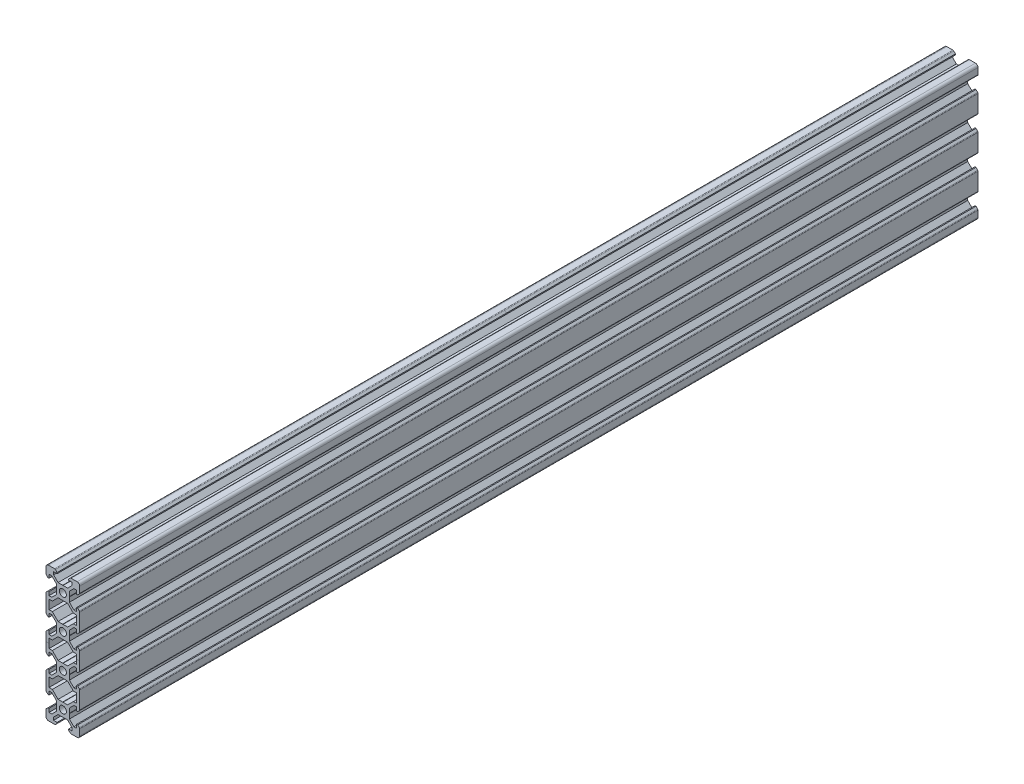
SolidWorks part; units mm, degrees
material "6063-T5"
ref_plane "Front" through (0, 0, 0) normal (0, 0, 1) x (1, 0, 0)
ref_plane "Top" through (0, 0, 0) normal (0, 1, 0) x (1, 0, 0)
ref_plane "Right" through (0, 0, 0) normal (1, 0, 0) x (0, 0, -1)
sketch "Sketch1" plane through (0, 0, 0) normal (0, 0, 1) x (1, 0, 0)
  line L0 (-8.5, 10) -> (-10, 8.5) construction
  line L1 (-8.5, 10) -> (-4.8628, 10)
  line L2 (-10, 8.5) -> (-10, 4.8628)
  line L3 (25.9287, -20) -> (-28.3599, -20) construction
  line L4 (10, 8.5) -> (10, 4.8628)
  line L5 (-10, 10) -> (10, -10) construction
  line L6 (-10, -10) -> (10, 10) construction
  line L7 (8.2, -5.5) -> (8.2, -3.3865)
  line L8 (-8.2, -5.5) -> (-8.2, -3.3865)
  line L9 (-5.5, 8.2) -> (-3.3865, 8.2)
  line L10 (-8.2, -12.7) -> (-8.2, -7.3)
  line L11 (-3.9005, 2.8395) -> (-6.561, 5.5)
  line L12 (-6.561, 5.5) -> (-8.2, 5.5)
  line L13 (-2.8395, -3.9005) -> (-0.1, -3.9005)
  line L14 (-3.9005, -2.8395) -> (-3.9005, -0.1)
  line L15 (-2.8395, 3.9005) -> (-0.1, 3.9005)
  line L16 (3.9005, -2.8395) -> (3.9005, -0.1)
  line L17 (-8.2, 3.3865) -> (-8.81, 3.3865)
  line L18 (-8.81, 3.3865) -> (-9.7976, 4.3741)
  line L19 (8.5, 10) -> (10, 8.5) construction
  line L20 (-2.8395, 3.9005) -> (-5.5, 6.561)
  line L21 (-5.5, 6.561) -> (-5.5, 8.2)
  line L22 (-3.3865, 8.2) -> (-3.3865, 8.81)
  line L23 (-3.3865, 8.81) -> (-4.3741, 9.7976)
  line L24 (0, 24.069) -> (0, -33.8154) construction
  line L25 (3.3865, 8.81) -> (4.3741, 9.7976)
  line L26 (3.3865, 8.2) -> (3.3865, 8.81)
  line L27 (5.5, 6.561) -> (5.5, 8.2)
  line L28 (2.8395, 3.9005) -> (5.5, 6.561)
  line L29 (3.3865, 8.2) -> (5.5, 8.2)
  line L30 (4.8628, 10) -> (8.5, 10)
  line L31 (-0.1, 3.9005) -> (0, 3.8005)
  line L32 (0.1, 3.9005) -> (0, 3.8005)
  line L33 (0.1, 3.9005) -> (2.8395, 3.9005)
  line L34 (25.9287, 0) -> (-28.3459, 0) construction
  line L35 (-0.1, -3.9005) -> (0, -3.8005)
  line L36 (0.1, -3.9005) -> (0, -3.8005)
  line L37 (0.1, -3.9005) -> (2.8395, -3.9005)
  line L38 (-3.9005, 0.1) -> (-3.8005, 0)
  line L39 (-3.8005, 0) -> (-3.9005, -0.1)
  line L40 (-3.9005, 0.1) -> (-3.9005, 2.8395)
  line L41 (3.9005, 0.1) -> (3.8005, 0)
  line L42 (3.8005, 0) -> (3.9005, -0.1)
  line L43 (3.9005, 0.1) -> (3.9005, 2.8395)
  line L44 (8.81, 3.3865) -> (9.7976, 4.3741)
  line L45 (8.2, 3.3865) -> (8.81, 3.3865)
  line L46 (6.561, 5.5) -> (8.2, 5.5)
  line L47 (3.9005, 2.8395) -> (6.561, 5.5)
  line L48 (2.8395, -3.9005) -> (5.5, -6.561)
  line L49 (3.9005, -2.8395) -> (6.561, -5.5)
  line L50 (-2.8395, -3.9005) -> (-5.5, -6.561)
  line L51 (-3.9005, -2.8395) -> (-6.561, -5.5)
  line L52 (6.561, -5.5) -> (8.2, -5.5)
  line L53 (-6.561, -5.5) -> (-8.2, -5.5)
  line L54 (-8.81, -3.3865) -> (-9.7976, -4.3741)
  line L55 (-8.2, -3.3865) -> (-8.81, -3.3865)
  line L56 (8.81, -3.3865) -> (9.7976, -4.3741)
  line L57 (8.2, -3.3865) -> (8.81, -3.3865)
  line L58 (8.2, 3.3865) -> (8.2, 5.5)
  line L59 (10, -4.8628) -> (10, -15.1372)
  line L60 (-8.2, 3.3865) -> (-8.2, 5.5)
  line L61 (-10, -4.8628) -> (-10, -15.1372)
  line L62 (-28.3459, -10) -> (-10, -10) construction
  line L63 (-3.9005, -20.1) -> (-3.9005, -22.8395)
  line L64 (-3.9005, -20.1) -> (-3.8005, -20)
  line L65 (-3.8005, -20) -> (-3.9005, -19.9)
  line L66 (3.9005, -20.1) -> (3.9005, -22.8395)
  line L67 (3.9005, -20.1) -> (3.8005, -20)
  line L68 (3.8005, -20) -> (3.9005, -19.9)
  line L69 (6.561, -14.5) -> (8.2, -14.5)
  line L70 (3.9005, -17.1605) -> (6.561, -14.5)
  line L71 (3.9005, -17.1605) -> (3.9005, -19.9)
  line L72 (-3.9005, -17.1605) -> (-3.9005, -19.9)
  line L73 (-3.9005, -17.1605) -> (-6.561, -14.5)
  line L74 (-6.561, -14.5) -> (-8.2, -14.5)
  line L75 (-8.2, -16.6135) -> (-8.81, -16.6135)
  line L76 (-8.81, -16.6135) -> (-9.7976, -15.6259)
  line L77 (8.2, -16.6135) -> (8.81, -16.6135)
  line L78 (8.81, -16.6135) -> (9.7976, -15.6259)
  line L79 (-2.8395, -16.0995) -> (-5.5, -13.439)
  line L80 (-2.8395, -16.0995) -> (-0.1, -16.0995)
  line L81 (-0.1, -16.0995) -> (0, -16.1995)
  line L82 (0.1, -16.0995) -> (0, -16.1995)
  line L83 (0.1, -16.0995) -> (2.8395, -16.0995)
  line L84 (2.8395, -16.0995) -> (5.5, -13.439)
  line L85 (-8.2, -16.6135) -> (-8.2, -14.5)
  line L86 (8.2, -16.6135) -> (8.2, -14.5)
  line L87 (2.8395, -23.9005) -> (5.5, -26.561)
  line L88 (-2.8395, -23.9005) -> (-5.5, -26.561)
  line L89 (-0.1, -23.9005) -> (0, -23.8005)
  line L90 (0.1, -23.9005) -> (0, -23.8005)
  line L91 (0.1, -23.9005) -> (2.8395, -23.9005)
  line L92 (-2.8395, -23.9005) -> (-0.1, -23.9005)
  line L93 (-8.2, -23.3865) -> (-8.2, -25.5)
  line L94 (-8.2, -23.3865) -> (-8.81, -23.3865)
  line L95 (-8.81, -23.3865) -> (-9.7976, -24.3741)
  line L96 (8.2, -23.3865) -> (8.2, -25.5)
  line L97 (8.2, -23.3865) -> (8.81, -23.3865)
  line L98 (8.81, -23.3865) -> (9.7976, -24.3741)
  line L99 (8.2, -27.3) -> (8.2, -32.7)
  line L100 (10, -35.1372) -> (10, -24.8628)
  line L101 (-10, -35.1372) -> (-10, -24.8628)
  line L102 (-8.2, -27.3) -> (-8.2, -32.7)
  line L103 (3.9005, -22.8395) -> (6.561, -25.5)
  line L104 (-3.9005, -22.8395) -> (-6.561, -25.5)
  line L105 (6.239, -27.3) -> (8.2, -27.3)
  line L106 (-6.239, -27.3) -> (-8.2, -27.3)
  line L107 (-6.561, -25.5) -> (-8.2, -25.5)
  line L108 (6.561, -25.5) -> (8.2, -25.5)
  line L109 (5.5, -26.561) -> (6.239, -27.3)
  line L110 (-5.5, -26.561) -> (-6.239, -27.3)
  line L111 (8.2, -34.5) -> (8.2, -36.6135)
  line L112 (8.2, -36.6135) -> (8.81, -36.6135)
  line L113 (8.81, -36.6135) -> (9.7976, -35.6259)
  line L114 (-8.2, -34.5) -> (-8.2, -36.6135)
  line L115 (-6.239, -7.3) -> (-8.2, -7.3)
  line L116 (-5.5, -6.561) -> (-6.239, -7.3)
  line L117 (6.239, -7.3) -> (8.2, -7.3)
  line L118 (5.5, -6.561) -> (6.239, -7.3)
  line L119 (-6.239, -12.7) -> (-8.2, -12.7)
  line L120 (-5.5, -13.439) -> (-6.239, -12.7)
  line L121 (5.5, -13.439) -> (6.239, -12.7)
  line L122 (6.239, -12.7) -> (8.2, -12.7)
  line L123 (8.2, -12.7) -> (8.2, -7.3)
  line L124 (-8.2, -36.6135) -> (-8.81, -36.6135)
  line L125 (10, -10) -> (25.9287, -10) construction
  line L126 (-8.81, -36.6135) -> (-9.7976, -35.6259)
  line L127 (-0.1, -56.0995) -> (0, -56.1995)
  line L128 (-0.1, -36.0995) -> (0, -36.1995)
  line L129 (0.1, -36.0995) -> (0, -36.1995)
  line L130 (0.1, -36.0995) -> (2.8395, -36.0995)
  line L131 (-6.561, -34.5) -> (-8.2, -34.5)
  line L132 (6.561, -34.5) -> (8.2, -34.5)
  line L133 (6.239, -32.7) -> (8.2, -32.7)
  line L134 (-6.239, -32.7) -> (-8.2, -32.7)
  line L135 (-5.5, -33.439) -> (-6.239, -32.7)
  line L136 (5.5, -33.439) -> (6.239, -32.7)
  line L137 (-26.6965, -30) -> (27.5921, -30) construction
  line L138 (0.1, -56.0995) -> (0, -56.1995)
  line L139 (0.1, -56.0995) -> (2.8395, -56.0995)
  line L140 (-2.8395, -56.0995) -> (-0.1, -56.0995)
  line L141 (0, -60) -> (0, -71.7864) construction
  line L142 (-3.8005, -60) -> (-3.9005, -59.9)
  line L143 (-3.9005, -60.1) -> (-3.8005, -60)
  line L144 (10, -68.5) -> (10, -64.8628)
  line L145 (0.1, -63.9005) -> (0, -63.8005)
  line L146 (-0.1, -63.9005) -> (0, -63.8005)
  line L147 (-2.8395, -63.9005) -> (-0.1, -63.9005)
  line L148 (0.1, -63.9005) -> (2.8395, -63.9005)
  line L149 (3.9005, -60.1) -> (3.9005, -62.8395)
  line L150 (3.9005, -60.1) -> (3.8005, -60)
  line L151 (3.8005, -60) -> (3.9005, -59.9)
  line L152 (3.9005, -57.1605) -> (3.9005, -59.9)
  line L153 (4.8628, -70) -> (8.5, -70)
  line L154 (3.3865, -68.81) -> (4.3741, -69.7976)
  line L155 (3.3865, -68.2) -> (3.3865, -68.81)
  line L156 (3.3865, -68.2) -> (5.5, -68.2)
  line L157 (-0.1, -43.9005) -> (0, -43.8005)
  line L158 (0.1, -43.9005) -> (0, -43.8005)
  line L159 (-2.8395, -43.9005) -> (-0.1, -43.9005)
  line L160 (0.1, -43.9005) -> (2.8395, -43.9005)
  line L161 (3.9005, -40.1) -> (3.8005, -40)
  line L162 (3.8005, -40) -> (3.9005, -39.9)
  line L163 (3.9005, -37.1605) -> (3.9005, -39.9)
  line L164 (3.9005, -40.1) -> (3.9005, -42.8395)
  line L165 (-2.8395, -36.0995) -> (-0.1, -36.0995)
  line L166 (-2.8395, -43.9005) -> (-5.5, -46.561)
  line L167 (-3.9005, -37.1605) -> (-3.9005, -39.9)
  line L168 (-3.8005, -40) -> (-3.9005, -39.9)
  line L169 (-3.9005, -40.1) -> (-3.8005, -40)
  line L170 (-3.9005, -42.8395) -> (-6.561, -45.5)
  line L171 (2.8395, -43.9005) -> (5.5, -46.561)
  line L172 (3.9005, -42.8395) -> (6.561, -45.5)
  line L173 (3.9005, -37.1605) -> (6.561, -34.5)
  line L174 (2.8395, -36.0995) -> (5.5, -33.439)
  line L175 (-3.9005, -42.8395) -> (-3.9005, -40.1)
  line L176 (-6.561, -34.5) -> (-3.9005, -37.1605)
  line L177 (-5.5, -33.439) -> (-2.8395, -36.0995)
  line L178 (5.5, -66.561) -> (5.5, -68.2)
  line L179 (6.561, -65.5) -> (8.2, -65.5)
  line L180 (8.2, -63.3865) -> (8.2, -65.5)
  line L181 (8.81, -63.3865) -> (9.7976, -64.3741)
  line L182 (8.2, -63.3865) -> (8.81, -63.3865)
  line L183 (-8.2, -63.3865) -> (-8.81, -63.3865)
  line L184 (-8.81, -63.3865) -> (-9.7976, -64.3741)
  line L185 (-8.2, -63.3865) -> (-8.2, -65.5)
  line L186 (-6.561, -65.5) -> (-8.2, -65.5)
  line L187 (-5.5, -66.561) -> (-5.5, -68.2)
  line L188 (-5.5, -68.2) -> (-3.3865, -68.2)
  line L189 (-3.3865, -68.2) -> (-3.3865, -68.81)
  line L190 (-3.3865, -68.81) -> (-4.3741, -69.7976)
  line L191 (-10, -68.5) -> (-10, -64.8628)
  line L192 (-8.5, -70) -> (-4.8628, -70)
  line L193 (-8.2, -43.3865) -> (-8.81, -43.3865)
  line L194 (-8.81, -43.3865) -> (-9.7976, -44.3741)
  line L195 (-10, -55.1372) -> (-10, -44.8628)
  line L196 (-8.81, -56.6135) -> (-9.7976, -55.6259)
  line L197 (-8.2, -56.6135) -> (-8.81, -56.6135)
  line L198 (8.2, -56.6135) -> (8.81, -56.6135)
  line L199 (8.81, -56.6135) -> (9.7976, -55.6259)
  line L200 (8.2, -43.3865) -> (8.81, -43.3865)
  line L201 (8.81, -43.3865) -> (9.7976, -44.3741)
  line L202 (10, -55.1372) -> (10, -44.8628)
  line L203 (-8.2, -47.3) -> (-8.2, -52.7)
  line L204 (8.2, -47.3) -> (8.2, -52.7)
  line L205 (-6.239, -52.7) -> (-8.2, -52.7)
  line L206 (6.239, -52.7) -> (8.2, -52.7)
  line L207 (-6.561, -54.5) -> (-8.2, -54.5)
  line L208 (6.561, -54.5) -> (8.2, -54.5)
  line L209 (-3.9005, -60.1) -> (-3.9005, -62.8395)
  line L210 (-2.8395, -56.0995) -> (-5.5, -53.439)
  line L211 (3.9005, -57.1605) -> (6.561, -54.5)
  line L212 (2.8395, -56.0995) -> (5.5, -53.439)
  line L213 (5.5, -53.439) -> (6.239, -52.7)
  line L214 (-5.5, -53.439) -> (-6.239, -52.7)
  line L215 (-8.2, -43.3865) -> (-8.2, -45.5)
  line L216 (8.2, -43.3865) -> (8.2, -45.5)
  line L217 (-2.8395, -63.9005) -> (-5.5, -66.561)
  line L218 (-3.9005, -62.8395) -> (-6.561, -65.5)
  line L219 (2.8395, -63.9005) -> (5.5, -66.561)
  line L220 (3.9005, -62.8395) -> (6.561, -65.5)
  line L221 (-8.2, -54.5) -> (-8.2, -56.6135)
  line L222 (8.2, -54.5) -> (8.2, -56.6135)
  line L223 (6.239, -47.3) -> (8.2, -47.3)
  line L224 (-6.239, -47.3) -> (-8.2, -47.3)
  line L225 (-6.561, -45.5) -> (-8.2, -45.5)
  line L226 (-5.5, -46.561) -> (-6.239, -47.3)
  line L227 (6.561, -45.5) -> (8.2, -45.5)
  line L228 (5.5, -46.561) -> (6.239, -47.3)
  line L229 (-3.9005, -57.1605) -> (-3.9005, -59.9)
  line L230 (-3.9005, -57.1605) -> (-6.561, -54.5)
  circle A0 centre (0, 0) radius 2.1
  arc A1 (-8.5, 10) -> (-10, 8.5) centre (-8.5, 8.5) ccw
  arc A2 (10, 8.5) -> (8.5, 10) centre (8.5, 8.5) ccw
  arc A3 (-4.3741, 9.7976) -> (-4.8628, 10) centre (-4.8628, 9.3088) ccw
  arc A4 (4.8628, 10) -> (4.3741, 9.7976) centre (4.8628, 9.3088) ccw
  circle A5 centre (0, -20) radius 2.1
  arc A6 (9.7976, 4.3741) -> (10, 4.8628) centre (9.3088, 4.8628) ccw
  arc A7 (-10, 4.8628) -> (-9.7976, 4.3741) centre (-9.3088, 4.8628) ccw
  arc A8 (-10, -4.8628) -> (-9.7976, -4.3741) centre (-9.3088, -4.8628) cw
  arc A9 (9.7976, -4.3741) -> (10, -4.8628) centre (9.3088, -4.8628) cw
  arc A10 (-10, -15.1372) -> (-9.7976, -15.6259) centre (-9.3088, -15.1372) ccw
  arc A11 (9.7976, -15.6259) -> (10, -15.1372) centre (9.3088, -15.1372) ccw
  arc A12 (-10, -24.8628) -> (-9.7976, -24.3741) centre (-9.3088, -24.8628) cw
  arc A13 (9.7976, -24.3741) -> (10, -24.8628) centre (9.3088, -24.8628) cw
  arc A14 (9.7976, -35.6259) -> (10, -35.1372) centre (9.3088, -35.1372) ccw
  arc A15 (-10, -35.1372) -> (-9.7976, -35.6259) centre (-9.3088, -35.1372) ccw
  circle A16 centre (0, -40) radius 2.1
  circle A17 centre (0, -60) radius 2.1
  arc A18 (10, -68.5) -> (8.5, -70) centre (8.5, -68.5) cw
  arc A19 (4.8628, -70) -> (4.3741, -69.7976) centre (4.8628, -69.3088) cw
  arc A20 (9.7976, -64.3741) -> (10, -64.8628) centre (9.3088, -64.8628) cw
  arc A21 (-10, -64.8628) -> (-9.7976, -64.3741) centre (-9.3088, -64.8628) cw
  arc A22 (-4.3741, -69.7976) -> (-4.8628, -70) centre (-4.8628, -69.3088) cw
  arc A23 (-8.5, -70) -> (-10, -68.5) centre (-8.5, -68.5) cw
  arc A24 (-10, -44.8628) -> (-9.7976, -44.3741) centre (-9.3088, -44.8628) cw
  arc A25 (-10, -55.1372) -> (-9.7976, -55.6259) centre (-9.3088, -55.1372) ccw
  arc A26 (9.7976, -55.6259) -> (10, -55.1372) centre (9.3088, -55.1372) ccw
  arc A27 (9.7976, -44.3741) -> (10, -44.8628) centre (9.3088, -44.8628) cw
  point P17 (-9.25, 9.25)
  point P21 (9.25, 9.25)
  point P181 (-10, -30)
  dimension "D2" = 4.2
  dimension "D4" = 1.5
  dimension "D3" = 20
  dimension "D5" = 0.529
  dimension "D6" = 6.773
  dimension "D7" = 90
  dimension "D8" = 11
  dimension "D9" = 0.61
  dimension "D10" = 0.1
  dimension "D11" = 0.1
  dimension "D12" = 0.1
  dimension "D13" = 0.1
  dimension "D14" = 5.679
  dimension "D15" = 1.639
  dimension "D16" = 1.8
  dimension "D17" = 90
  dimension "D18" = 6.773
  dimension "D19" = 90
  dimension "D20" = 20
  dimension "D21" = 1.8
extrude "Boss-Extrude2" add sketch "Sketch1" along normal blind 533
sketch "Sketch2" plane through (0, 0, 533) normal (0, 0, 1) x (1, 0, 0)
  line L0 (-10, -30) -> (10, -30)
  line L1 (-10, -24.8628) -> (-10, -35.1372) construction
  line L2 (10, -35.1372) -> (10, -24.8628) construction
split line "SideFixture1 - SplitLine"
sketch "Sketch3" plane through (0, 0, 0) normal (0, 0, -1) x (-1, 0, 0)
  line L0 (-10, -30) -> (10, -30)
  line L1 (-10, -35.1372) -> (-10, -24.8628) construction
  line L2 (10, -24.8628) -> (10, -35.1372) construction
split line "SideFixture2 - SplitLine"
sketch "Sketch4" plane through (0, 10, 0) normal (0, 1, 0) x (1, 0, 0)
  line L0 (8.5, -266.5) -> (-8.5, -266.5)
  line L1 (8.5, -533) -> (8.5, 0) construction
  line L2 (-8.5, -533) -> (-8.5, 0) construction
split line "SideFixture3 - SplitLine"
equation "\"base-xwidth\"= 455mm"
equation "\"base-yheight\" = 533mm"
equation "\"base-zdepth\"= 377mm"
equation "\"D1@Boss-Extrude2\"=\"base-yheight\""
